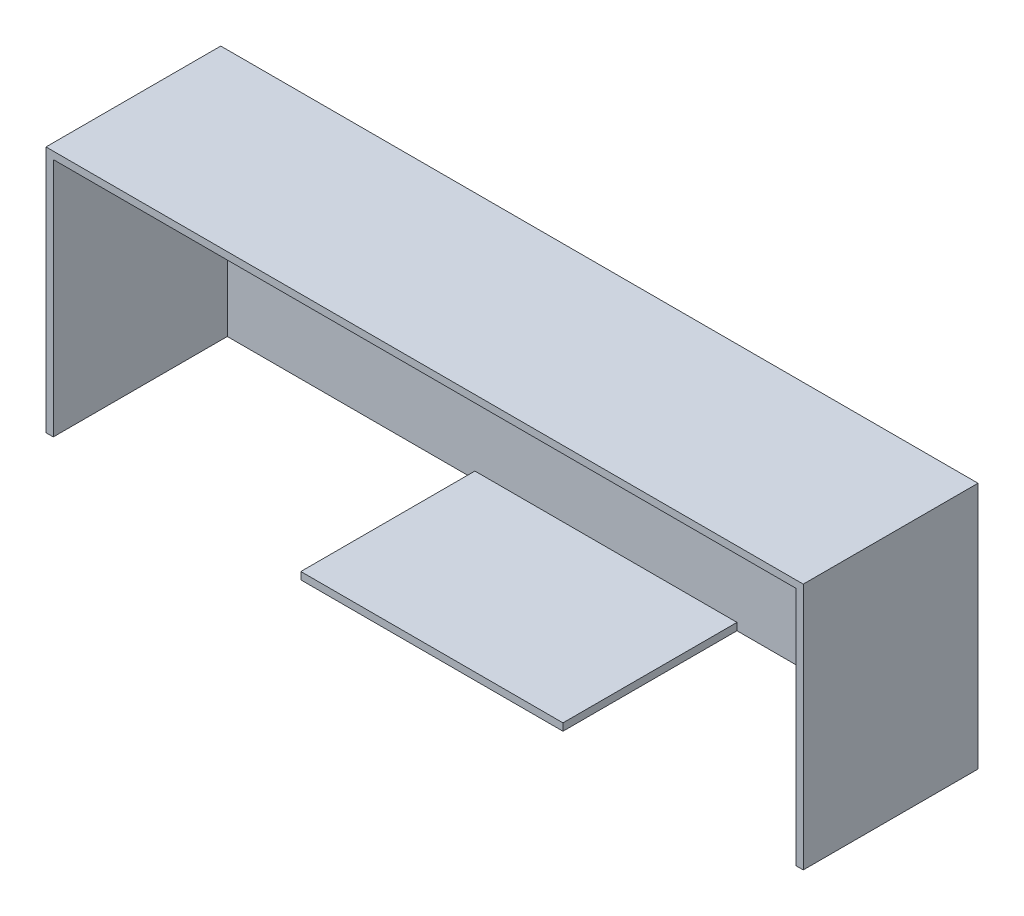
SolidWorks part; units mm, degrees
ref_plane "Front Plane" through (0, 0, 0) normal (0, 0, 1) x (1, 0, 0)
ref_plane "Top Plane" through (0, 0, 0) normal (0, 1, 0) x (1, 0, 0)
ref_plane "Right Plane" through (0, 0, 0) normal (1, 0, 0) x (0, 0, -1)
sketch "Sketch1" plane through (0, 0, 0) normal (0, 0, 1) x (1, 0, 0)
  line L3 (-94.0451, 6.35) -> (566.3549, 6.35)
  line L5 (128.2049, -209.55) -> (356.8049, -209.55)
  line L6 (128.2049, -209.55) -> (128.2049, -203.2)
  line L7 (128.2049, -203.2) -> (356.8049, -203.2)
  line L8 (356.8049, -209.55) -> (356.8049, -203.2)
  line L9 (560.0049, 0) -> (560.0049, -209.55)
  line L10 (560.0049, -209.55) -> (566.3549, -209.55)
  line L11 (566.3549, -209.55) -> (566.3549, 6.35)
  line L12 (560.0049, 0) -> (-87.6951, 0)
  line L13 (356.8049, -209.55) -> (560.0049, -209.55)
  line L14 (-87.6951, 0) -> (-87.6951, -209.55)
  line L15 (-87.6951, -209.55) -> (-94.0451, -209.55)
  line L16 (-94.0451, -209.55) -> (-94.0451, 6.35)
  dimension "D1" = 228.6
  dimension "D2" = 6.35
  dimension "D3" = 6.35
  dimension "D4" = 215.9
  dimension "D5" = 203.2
  dimension "D6" = 6.35
  dimension "D8" = 203.2
  dimension "D9" = 6.35
extrude "Boss-Extrude1" add sketch "Sketch1" along normal blind 152.4
sketch "Sketch3" plane through (0, 0, 0) normal (0, 0, -1) x (-1, 0, 0)
  line L2 (-560.0049, -209.55) -> (-560.0049, 0)
  line L4 (-560.0049, -209.55) -> (87.6951, -209.55)
  line L5 (87.6951, -209.55) -> (87.6951, 0)
  line L6 (87.6951, 0) -> (-560.0049, 0)
extrude "Boss-Extrude2" add sketch "Sketch3" against normal blind 0.635
